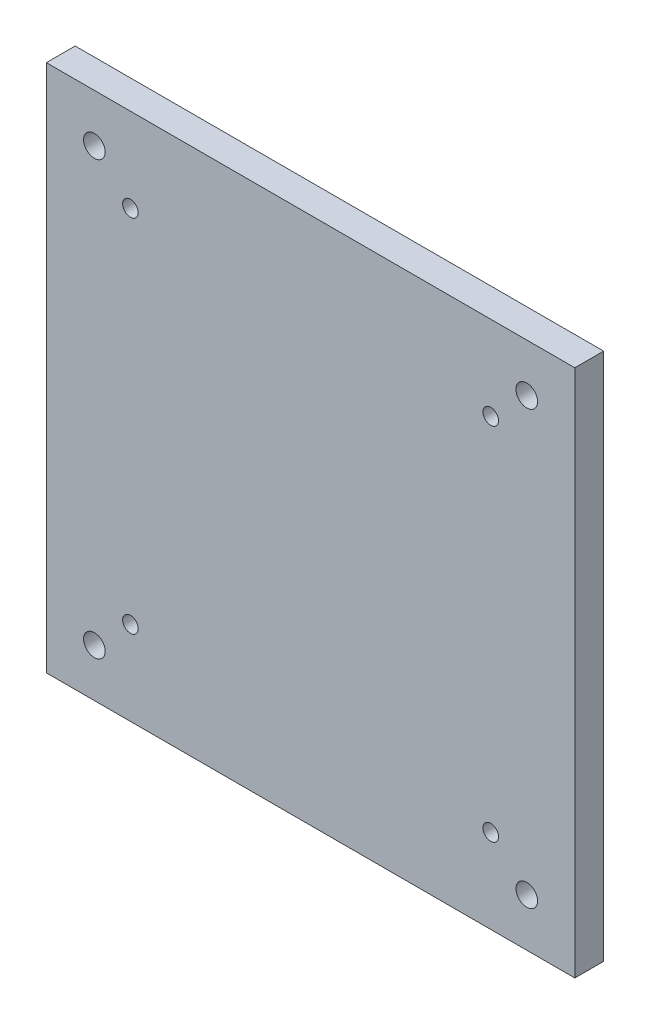
SolidWorks part; units mm, degrees
material "6061-T6 (SS)"
ref_plane "前视基准面" through (0, 0, 0) normal (0, 0, 1) x (1, 0, 0)
ref_plane "上视基准面" through (0, 0, 0) normal (0, 1, 0) x (1, 0, 0)
ref_plane "右视基准面" through (0, 0, 0) normal (1, 0, 0) x (0, 0, -1)
other "Configuration Table"
sketch "草图1" plane through (0, 0, 0) normal (0, 0, 1) x (1, 0, 0)
  line L0 (-110, -110) -> (110, -110)
  line L1 (110, -110) -> (110, 110)
  line L2 (110, 110) -> (-110, 110)
  line L3 (-110, 110) -> (-110, -110)
extrude "凸台-拉伸1" add sketch "草图1" along normal blind 12
sketch "草图2" plane through (0, 0, 0) normal (0, 0, -1) x (-1, 0, 0)
  circle A0 centre (90, -90) radius 4.5
  circle A1 centre (90, 90) radius 4.5
  circle A2 centre (-90, -90) radius 4.5
  circle A3 centre (-90, 90) radius 4.5
  circle A4 centre (75, -75) radius 3.25
  circle A5 centre (75, 75) radius 3.25
  circle A6 centre (-75, -75) radius 3.25
  circle A7 centre (-75, 75) radius 3.25
extrude "切除-拉伸1" cut sketch "草图2" against normal blind 13
sketch "草图3" plane through (0, 0, 0) normal (0, 0, -1) x (-1, 0, 0)
  circle A0 centre (75, -75) radius 5.5
  circle A1 centre (75, 75) radius 5.5
  circle A2 centre (-75, -75) radius 5.5
  circle A3 centre (-75, 75) radius 5.5
extrude "切除-拉伸2" cut sketch "草图3" against normal blind 6.5
